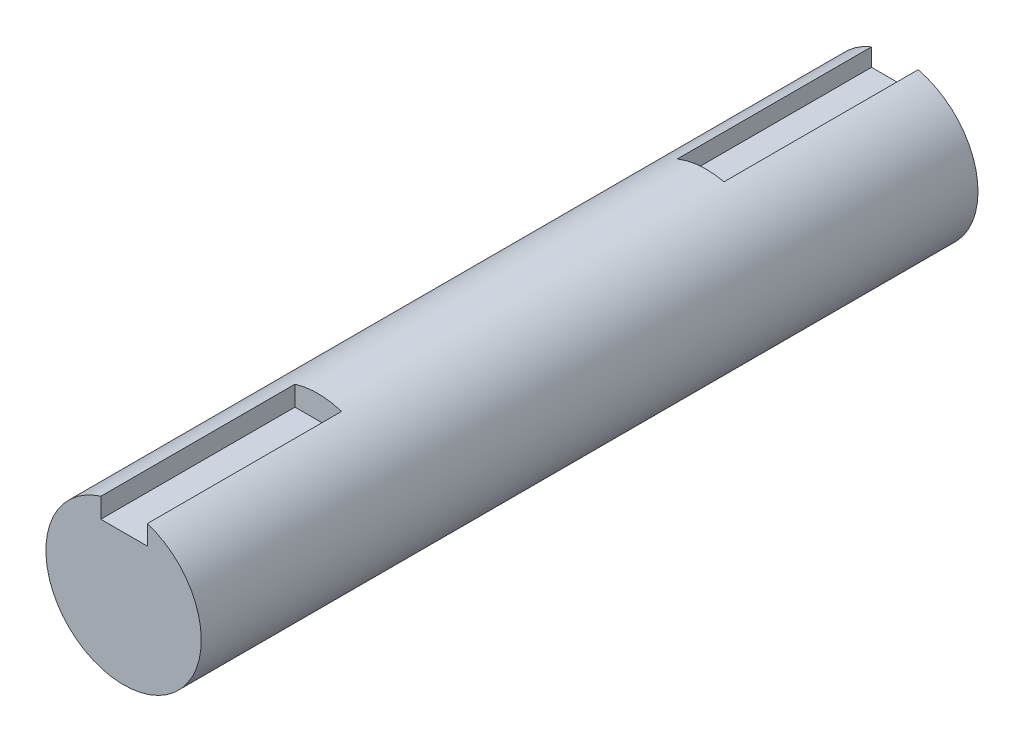
SolidWorks part; units mm, degrees
ref_plane "Front Plane" through (0, 0, 0) normal (0, 0, 1) x (1, 0, 0)
ref_plane "Top Plane" through (0, 0, 0) normal (0, 1, 0) x (1, 0, 0)
ref_plane "Right Plane" through (0, 0, 0) normal (1, 0, 0) x (0, 0, -1)
sketch "Sketch1" plane through (0, 0, 0) normal (0, 0, 1) x (1, 0, 0)
  circle A0 centre (0, 0) radius 10
  dimension "D1" = 20
extrude "Shaft_D20x100" add sketch "Sketch1" along normal blind 100
sketch "Sketch3" plane through (0, 0, 0) normal (0, 0, -1) x (-1, 0, 0)
  line L0 (3.7068, 10) -> (-2.2932, 10)
  line L1 (-2.2932, 10) -> (-2.2932, 7)
  line L2 (-2.2932, 7) -> (3.7068, 7)
  line L3 (3.7068, 7) -> (3.7068, 10)
  point P3 (0.7068, 10)
  dimension "D1" = 6
  dimension "D2" = 3
extrude "Keyway_6x25" cut sketch "Sketch3" against normal blind 25
sketch "Sketch4" plane through (0, 0, 100) normal (0, 0, 1) x (1, 0, 0)
  line L0 (3.0639, 10) -> (-2.9361, 10)
  line L1 (-2.9361, 10) -> (-2.9361, 7)
  line L2 (-2.9361, 7) -> (3.0639, 7)
  line L3 (3.0639, 7) -> (3.0639, 10)
  point P3 (0.0639, 10)
  dimension "D1" = 6
  dimension "D2" = 3
extrude "keywat2_6x25" cut sketch "Sketch4" against normal blind 25
